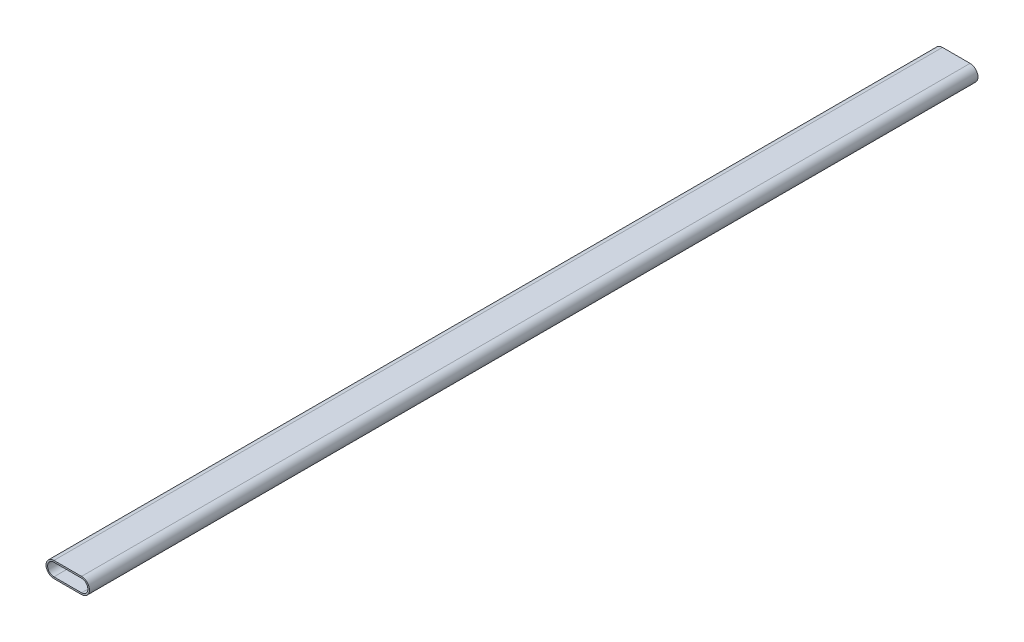
SolidWorks part; units mm, degrees
ref_plane "Front Plane" through (0, 0, 0) normal (0, 0, 1) x (1, 0, 0)
ref_plane "Top Plane" through (0, 0, 0) normal (0, 1, 0) x (1, 0, 0)
ref_plane "Right Plane" through (0, 0, 0) normal (1, 0, 0) x (0, 0, -1)
sketch "Sketch1" plane through (0, 0, 0) normal (0, 0, 1) x (1, 0, 0)
  line L0 (0, 0) -> (21, 0) construction
  line L1 (0, 6) -> (21, 6)
  line L2 (0, -6) -> (21, -6)
  line L3 (0, 4.8) -> (21, 4.8)
  line L4 (0, -4.8) -> (21, -4.8)
  arc A0 (0, 6) -> (0, -6) centre (0, 0) ccw
  arc A1 (21, -6) -> (21, 6) centre (21, 0) ccw
  arc A2 (21, -4.8) -> (21, 4.8) centre (21, 0) ccw
  arc A3 (0, 4.8) -> (0, -4.8) centre (0, 0) ccw
  point P3 (10.5, 0)
  dimension "D1" = 12
  dimension "D2" = 21
  dimension "D3" = 1.2
extrude "Boss-Extrude1" add sketch "Sketch1" along normal blind 675
